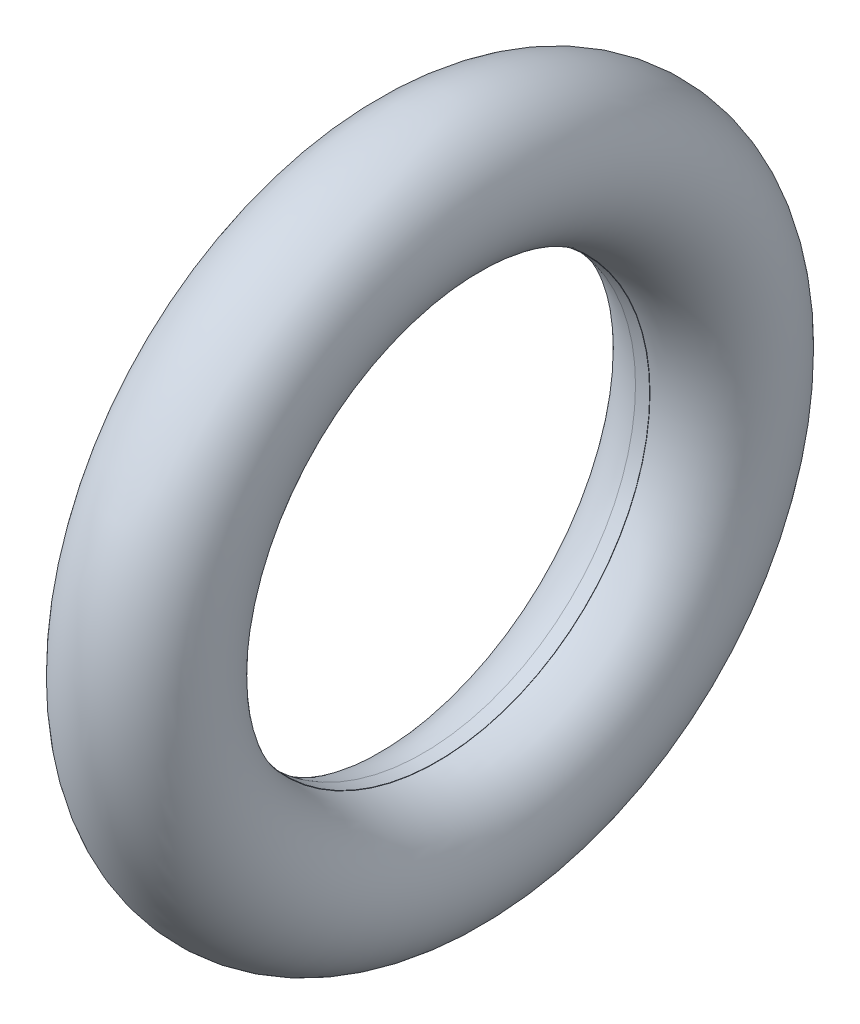
SolidWorks part; units mm, degrees
material "Rubber"
ref_plane "Front Plane" through (0, 0, 0) normal (0, 0, 1) x (1, 0, 0)
ref_plane "Top Plane" through (0, 0, 0) normal (0, 1, 0) x (1, 0, 0)
ref_plane "Right Plane" through (0, 0, 0) normal (1, 0, 0) x (0, 0, -1)
sketch "Sketch1" plane through (0, 0, 0) normal (0, 0, 1) x (1, 0, 0)
  line L0 (0, 0) -> (2, 0) construction
  line L1 (1, 0) -> (1, 3) construction
  line L2 (1, 3) -> (1, 4) construction
  line L3 (1, 4) -> (1, 5) construction
  line L4 (0, 4) -> (2, 4) construction
  line L5 (0.9, 3) -> (1, 3)
  line L6 (1, 3) -> (1.1, 3)
  line L7 (1.1, 3) -> (1.1, 3.005)
  line L8 (0.9, 3) -> (0.9, 3.005)
  circle A0 centre (1, 4) radius 1 construction
  arc A1 (0.9, 3.005) -> (1.1, 3.005) centre (1, 4) cw
  dimension "D1" = 2
  dimension "D2" = 5
  dimension "D3" = 0.1
revolve "Revolve1" add sketch "Sketch1" angle 360 about L0
move or copy body "Body-Move/Copy1" bodies to move or copy 101 parameters "D1"=0, "D2"=0, "D3"=0
equation "\"D2@Sketch1\"= \"r_small_wheel@wheel_assembly-1.Assembly@Wheels-2.Assembly\""
